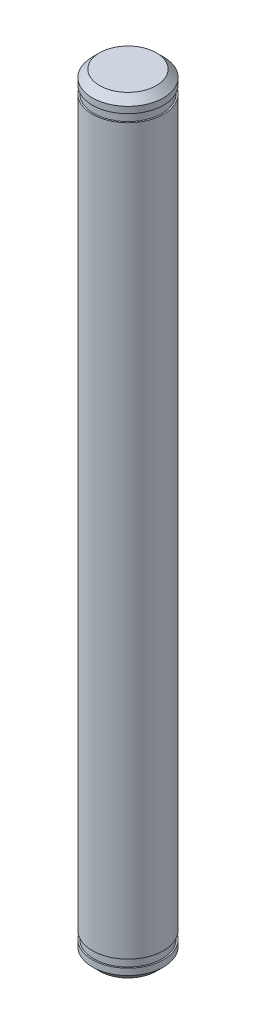
SolidWorks part; units mm, degrees
ref_plane "前视基准面" through (0, 0, 0) normal (0, 0, 1) x (1, 0, 0)
ref_plane "上视基准面" through (0, 0, 0) normal (0, 1, 0) x (1, 0, 0)
ref_plane "右视基准面" through (0, 0, 0) normal (1, 0, 0) x (0, 0, -1)
other "Configuration Table"
sketch "草图1" plane through (0, 0, 0) normal (0, 0, 1) x (1, 0, 0)
  line L0 (0, 17.9143) -> (0, -10.0949) construction
  line L1 (0, 54) -> (5, 54)
  line L2 (5, 54) -> (5, 30)
  line L4 (5, 30) -> (5, -30)
  line L6 (5, -30) -> (5, -54)
  line L7 (5, -54) -> (0, -54)
  line L8 (0, 0) -> (25.4592, 0) construction
  line L9 (0, 54) -> (0, -54)
  dimension "D1" = 5
  dimension "D3" = 60
  dimension "D4" = 24
  dimension "D5" = 24
revolve "旋转1" add sketch "草图1" angle 360 about L9
chamfer "倒角1" distance 1 angle 45 2 edges at (-5, -54, 0) (-5, 54, 0)
ref_plane "基准面1" through (0, 0, 0) normal (0, 1, 0) x (1, 0, 0)
sketch "草图2" plane through (0, 54, 0) normal (0, 1, 0) x (1, 0, 0)
  circle A0 centre (0, 0) radius 4.8
  circle A1 centre (0, 0) radius 5 construction
  circle A2 centre (0, 0) radius 5
  dimension "D1" = 9.6
extrude "切除-拉伸1" cut sketch "草图2" along normal blind 1.1 from offset 3 offset against normal yes
mirror "镜向1" about plane through (0, 0, 0) normal (0, 1, 0) of "切除-拉伸1"
